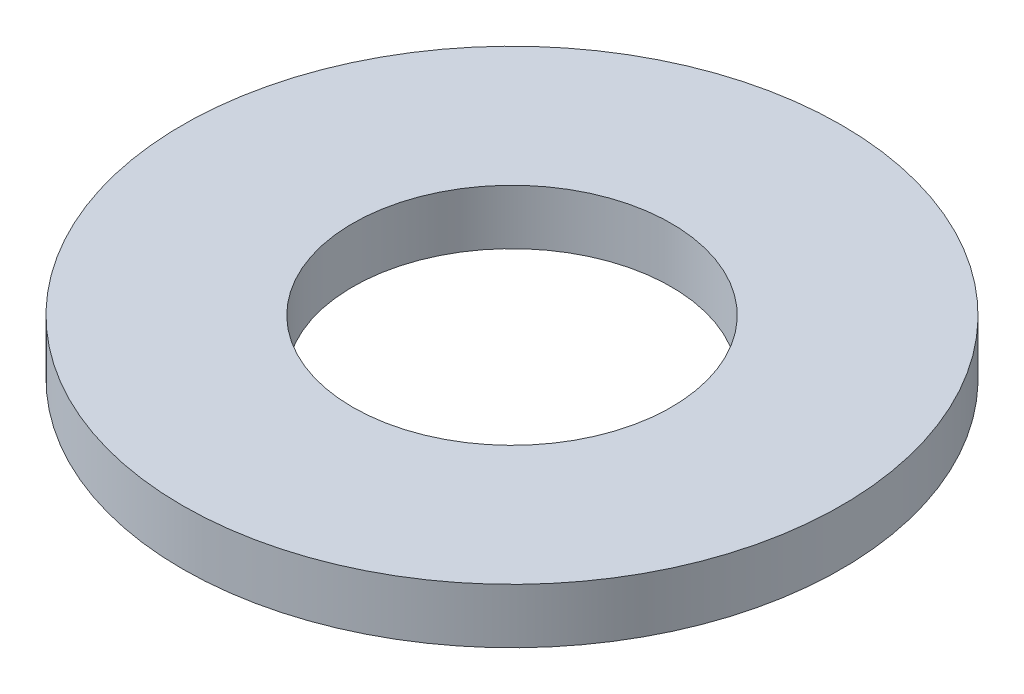
SolidWorks part; units mm, degrees
material "Alloy Steel"
ref_plane "정면" through (0, 0, 0) normal (0, 0, 1) x (1, 0, 0)
ref_plane "윗면" through (0, 0, 0) normal (0, 1, 0) x (1, 0, 0)
ref_plane "우측면" through (0, 0, 0) normal (1, 0, 0) x (0, 0, -1)
sketch "Sketch1" plane through (0, 0, 0) normal (0, 1, 0) x (1, 0, 0)
  circle A0 centre (0, 0) radius 1.45
  circle A1 centre (0, 0) radius 3
  circle A2 centre (0, 0) radius 1.25 construction
  dimension "M" = 2.5
  dimension "ID" = 2.9
  dimension "OD" = 6
extrude "Extrude1" add sketch "Sketch1" along normal blind 0.5
equation "\"Mass\"= \"SW-질량\" / 1000"
